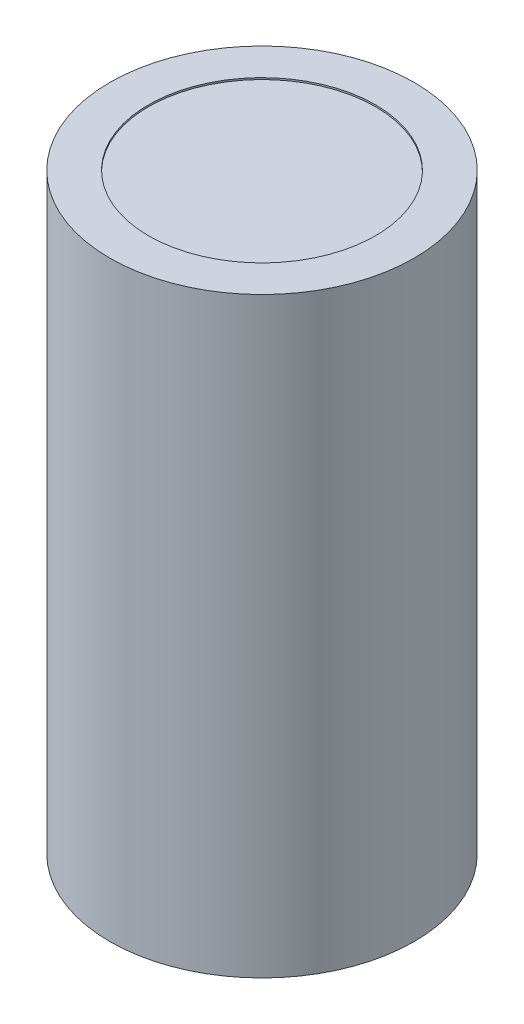
SolidWorks part; units mm, degrees
ref_plane "Front Plane" through (0, 0, 0) normal (0, 0, 1) x (1, 0, 0)
ref_plane "Top Plane" through (0, 0, 0) normal (0, 1, 0) x (1, 0, 0)
ref_plane "Right Plane" through (0, 0, 0) normal (1, 0, 0) x (0, 0, -1)
sketch "Sketch1" plane through (0, 0, 0) normal (0, 1, 0) x (1, 0, 0)
  circle A0 centre (0, 0) radius 9
  dimension "D1" = 18
extrude "Boss-Extrude1" add sketch "Sketch1" along normal blind 35
sketch "Sketch2" plane through (0, 35, 0) normal (0, 1, 0) x (1, 0, 0)
  circle A0 centre (0, 0) radius 6.7114
extrude "Cut-Extrude1" cut sketch "Sketch2" against normal blind 0.1
sketch "Sketch3" plane through (0, 0, 0) normal (0, -1, 0) x (1, 0, 0)
  circle A0 centre (0, 0) radius 7.3184
extrude "Cut-Extrude2" cut sketch "Sketch3" against normal blind 0.1
